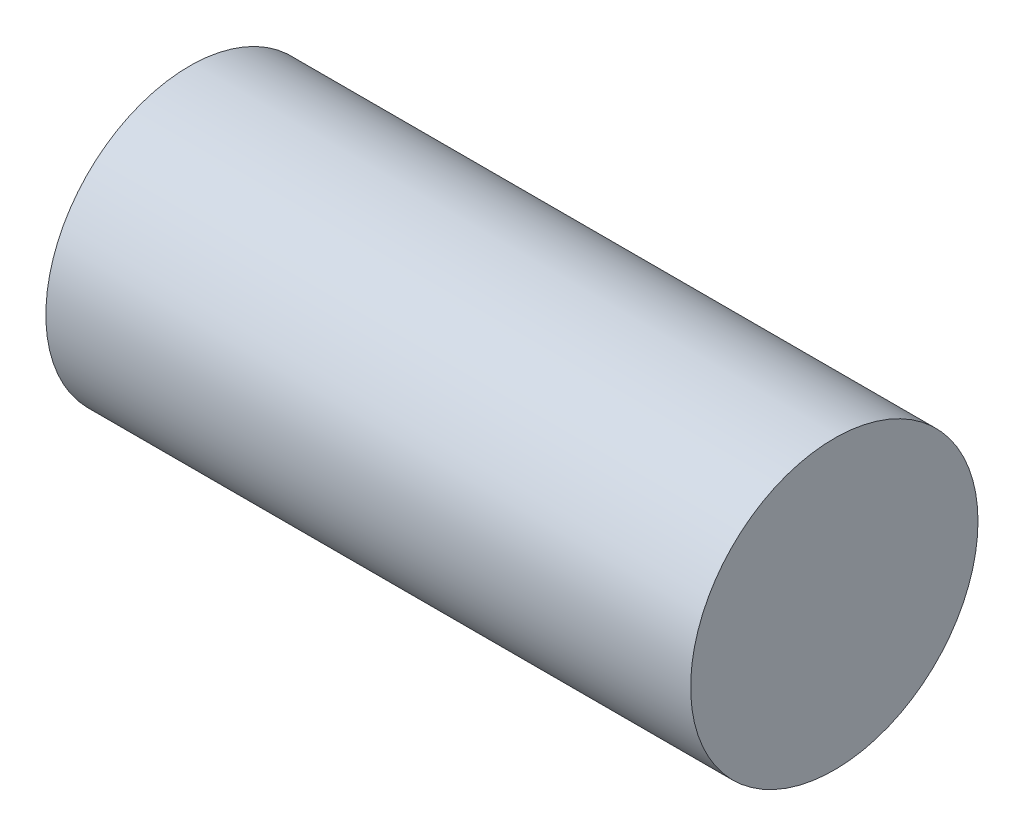
SolidWorks part; units mm, degrees
material "6061-T6 (SS)"
ref_plane "Front Plane" through (0, 0, 0) normal (0, 0, 1) x (1, 0, 0)
ref_plane "Top Plane" through (0, 0, 0) normal (0, 1, 0) x (1, 0, 0)
ref_plane "Right Plane" through (0, 0, 0) normal (1, 0, 0) x (0, 0, -1)
sketch "Sketch1" plane through (0, 0, 0) normal (1, 0, 0) x (0, 0, -1)
  circle A0 centre (0, 0) radius 6.35
  dimension "D1" = 12.7
extrude "Boss-Extrude1" add sketch "Sketch1" along normal blind 28.4988
